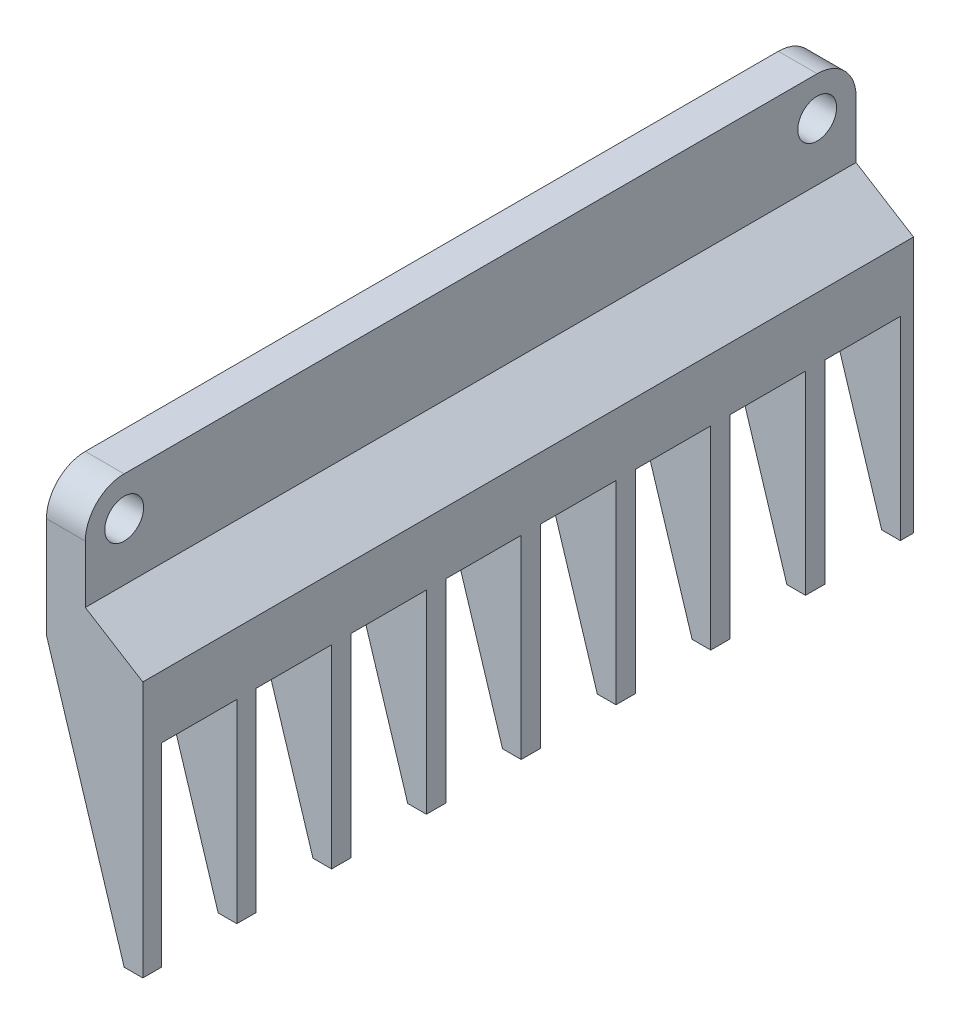
SolidWorks part; units mm, degrees
ref_plane "Front Plane" through (0, 0, 0) normal (0, 0, 1) x (1, 0, 0)
ref_plane "Top Plane" through (0, 0, 0) normal (0, 1, 0) x (1, 0, 0)
ref_plane "Right Plane" through (0, 0, 0) normal (1, 0, 0) x (0, 0, -1)
sketch "Sketch1" plane through (0, 0, 0) normal (0, 0, 1) x (1, 0, 0)
  line L0 (0, 0) -> (3.048, 0)
  line L1 (3.048, 0) -> (3.048, 41.91)
  line L2 (3.048, 41.91) -> (-6.35, 47.752)
  line L3 (-6.35, 47.752) -> (-6.35, 63.5)
  line L4 (-6.35, 63.5) -> (-12.7, 63.5)
  line L5 (-12.7, 63.5) -> (-12.7, 40.64)
  line L6 (-12.7, 40.64) -> (0, 0)
  dimension "D1" = 3.048
  dimension "D2" = 6.35
  dimension "D3" = 40.64
  dimension "D4" = 15.748
  dimension "D5" = 21.59
  dimension "D6" = 15.748
  dimension "D7" = 63.5
extrude "Boss-Extrude1" add sketch "Sketch1" along normal blind 125.984
fillet "Fillet1" radius 6.35 2 edges at (-9.525, 63.5, 0) (-9.525, 63.5, 125.984)
sketch "Sketch6" plane through (-6.35, 0, 0) normal (1, 0, 0) x (0, 0, -1)
  circle A0 centre (-119.634, 57.15) radius 3.175
  circle A1 centre (-6.35, 57.15) radius 3.175
  dimension "D1" = 6.35
  dimension "D2" = 6.35
extrude "Cut-Extrude2" cut sketch "Sketch6" against normal mid plane 125.984
sketch "Sketch7" plane through (3.048, 0, 0) normal (1, 0, 0) x (0, 0, -1)
  line L0 (-125.984, 0) -> (-125.984, 41.91) construction
  line L1 (-122.936, 0) -> (-110.617, 0)
  line L2 (-122.936, 0) -> (-122.936, 31.75)
  line L3 (-122.936, 31.75) -> (-110.617, 31.75)
  line L4 (-110.617, 0) -> (-110.617, 31.75)
  line L5 (-107.442, 0) -> (-107.442, 31.75)
  line L6 (-107.442, 0) -> (-95.123, 0)
  line L7 (-95.123, 0) -> (-95.123, 31.75)
  line L8 (-107.442, 31.75) -> (-95.123, 31.75)
  line L9 (-91.948, 0) -> (-91.948, 31.75)
  line L10 (-91.948, 0) -> (-79.629, 0)
  line L11 (-79.629, 0) -> (-79.629, 31.75)
  line L12 (-91.948, 31.75) -> (-79.629, 31.75)
  line L13 (-76.454, 0) -> (-76.454, 31.75)
  line L14 (-76.454, 0) -> (-64.135, 0)
  line L15 (-64.135, 0) -> (-64.135, 31.75)
  line L16 (-76.454, 31.75) -> (-64.135, 31.75)
  line L17 (-60.96, 0) -> (-60.96, 31.75)
  line L18 (-60.96, 0) -> (-48.641, 0)
  line L19 (-48.641, 0) -> (-48.641, 31.75)
  line L20 (-60.96, 31.75) -> (-48.641, 31.75)
  line L21 (-45.466, 0) -> (-45.466, 31.75)
  line L22 (-45.466, 0) -> (-33.147, 0)
  line L23 (-33.147, 0) -> (-33.147, 31.75)
  line L24 (-45.466, 31.75) -> (-33.147, 31.75)
  line L25 (-29.972, 0) -> (-29.972, 31.75)
  line L26 (-29.972, 0) -> (-17.653, 0)
  line L27 (-17.653, 0) -> (-17.653, 31.75)
  line L28 (-29.972, 31.75) -> (-17.653, 31.75)
  line L29 (-14.478, 0) -> (-14.478, 31.75)
  line L30 (-14.478, 0) -> (-2.159, 0)
  line L31 (-2.159, 0) -> (-2.159, 31.75)
  line L32 (-14.478, 31.75) -> (-2.159, 31.75)
  line L33 (-125.984, 0) -> (0, 0) construction
  line L34 (-125.984, 0) -> (0, 0)
  line M36 (-125.984, 0) -> (0, 0)
  dimension "D1" = 31.75
  dimension "D2" = 12.319
  dimension "D3" = 3.048
  dimension "D5" = 15.494
  dimension "D6" = 0
  dimension "D4" = 8
extrude "Cut-Extrude3" cut sketch "Sketch7" against normal through all contours L4 L3 L2 M36 | L8 L5 L7 M36 | L12 L9 L11 M36 | L16 L13 L15 M36 | L20 L17 L19 M36 | L24 L21 L23 M36 | L28 L25 L27 M36 | L32 L29 L31 M36
